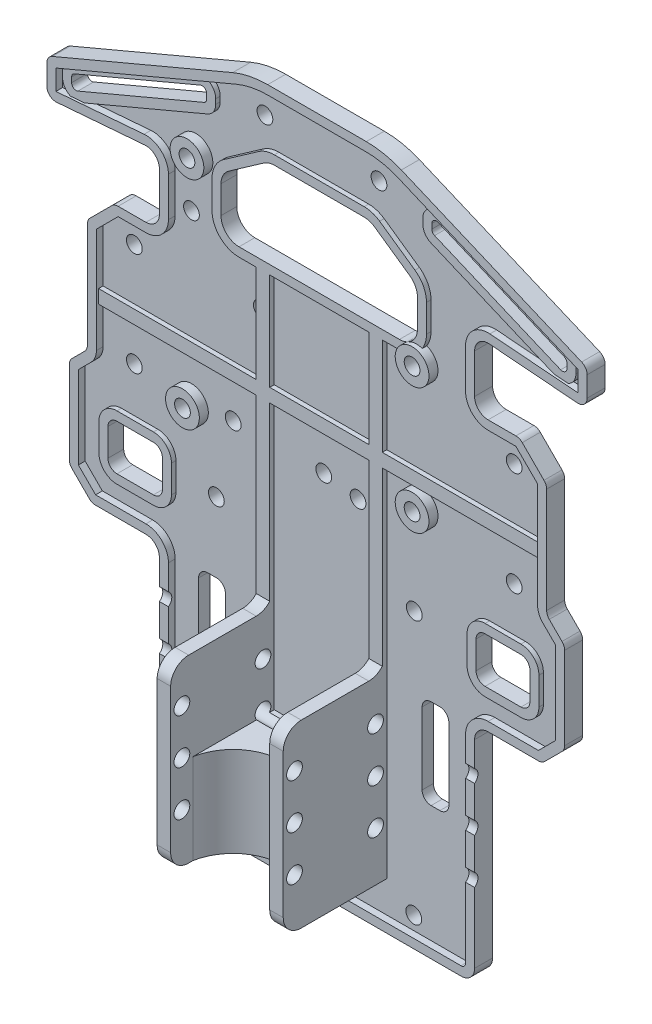
SolidWorks part; units mm, degrees
ref_plane "Front Plane" through (0, 0, 0) normal (0, 0, 1) x (1, 0, 0)
ref_plane "Top Plane" through (0, 0, 0) normal (0, 1, 0) x (1, 0, 0)
ref_plane "Right Plane" through (0, 0, 0) normal (1, 0, 0) x (0, 0, -1)
sketch "Sketch1" plane through (0, 0, 0) normal (0, 0, 1) x (1, 0, 0)
  line L1 (-55, 30) -> (-35, 30) construction
  line L2 (-55, 30) -> (-55, -30) construction
  line L3 (-55, -30) -> (-35, -30) construction
  line L4 (55, 30) -> (55, -30) construction
  line L5 (-55, 30) -> (55, -30) construction
  line L6 (-55, -30) -> (55, 30) construction
  line L8 (-35, 41.7504) -> (-35, 33)
  line L10 (35, 41.7504) -> (35, 33)
  line L11 (-35, 45) -> (35, 30) construction
  line L12 (-35, 30) -> (35, 45) construction
  line L13 (-60, 70) -> (60, 70) construction
  line L14 (-60, 70) -> (-60, 45) construction
  line L15 (-60, 45) -> (-35, 45) construction
  line L16 (60, 70) -> (60, 45) construction
  line L17 (-60, 70) -> (60, 45) construction
  line L18 (-60, 45) -> (60, 70) construction
  line L20 (0, 57.5) -> (0, 37.5) construction
  line L21 (32, -80) -> (-32, -80)
  line L22 (35, -77) -> (35, -33)
  line L24 (-35, -77) -> (-35, -33)
  line L25 (35, -80) -> (-35, -30) construction
  line L26 (35, -30) -> (-35, -80) construction
  line L27 (0, 37.5) -> (0, 0) construction
  line L28 (0, 0) -> (0, -55) construction
  line L29 (35, 45) -> (60, 45) construction
  line L30 (35, 30) -> (55, 30) construction
  line L31 (35, -30) -> (55, -30) construction
  line L32 (-35, -30) -> (35, -30) construction
  line L33 (35, 30) -> (-35, 30) construction
  line L34 (-35, 45) -> (35, 45) construction
  line L35 (-60, 45.1664) -> (-60, 49.6735)
  line L36 (-58.7779, 51.516) -> (-18.7303, 68.425)
  line L37 (-10.9508, 70) -> (10.9508, 70)
  line L38 (18.7303, 68.425) -> (58.7779, 51.516)
  line L39 (60, 49.6735) -> (60, 45.1664)
  line L40 (57.8405, 43.1728) -> (38.2392, 44.7409)
  line L41 (-38.2392, 44.7409) -> (-57.8405, 43.1728)
  line L42 (-60, 51) -> (60, 51) construction
  line L43 (60, 43) -> (-60, 43) construction
  line L44 (0, 57.5) -> (0, 70) construction
  line L45 (-38, -30) -> (-49.1716, -30)
  line L46 (-50.5858, -29.4142) -> (-54.4142, -25.5858)
  line L47 (-55, -24.1716) -> (-55, -5.8284)
  line L48 (-54.4142, -4.4142) -> (-51.5858, -1.5858)
  line L49 (-51, -0.1716) -> (-51, 23.1716)
  line L50 (-50.4142, 24.5858) -> (-45.5858, 29.4142)
  line L51 (-44.1716, 30) -> (-38, 30)
  line L52 (0, -55) -> (0, 55) construction
  line L53 (44.1716, 30) -> (38, 30)
  line L54 (50.4142, 24.5858) -> (45.5858, 29.4142)
  line L55 (51, -0.1716) -> (51, 23.1716)
  line L56 (54.4142, -4.4142) -> (51.5858, -1.5858)
  line L57 (55, -24.1716) -> (55, -5.8284)
  line L58 (50.5858, -29.4142) -> (54.4142, -25.5858)
  line L59 (38, -30) -> (49.1716, -30)
  line L60 (-55, 0) -> (55, 0) construction
  arc A0 (60, 45.1664) -> (57.8405, 43.1728) centre (58, 45.1664) cw
  arc A1 (58.7779, 51.516) -> (60, 49.6735) centre (58, 49.6735) cw
  arc A2 (-60, 45.1664) -> (-57.8405, 43.1728) centre (-58, 45.1664) ccw
  arc A3 (-60, 49.6735) -> (-58.7779, 51.516) centre (-58, 49.6735) cw
  arc A4 (10.9508, 70) -> (18.7303, 68.425) centre (10.9508, 50) cw
  arc A5 (-18.7303, 68.425) -> (-10.9508, 70) centre (-10.9508, 50) cw
  arc A6 (-45.5858, 29.4142) -> (-44.1716, 30) centre (-44.1716, 28) cw
  arc A7 (-51, 23.1716) -> (-50.4142, 24.5858) centre (-49, 23.1716) cw
  arc A8 (-51.5858, -1.5858) -> (-51, -0.1716) centre (-53, -0.1716) ccw
  arc A9 (-55, -5.8284) -> (-54.4142, -4.4142) centre (-53, -5.8284) cw
  arc A10 (-54.4142, -25.5858) -> (-55, -24.1716) centre (-53, -24.1716) cw
  arc A11 (-49.1716, -30) -> (-50.5858, -29.4142) centre (-49.1716, -28) cw
  arc A12 (45.5858, 29.4142) -> (44.1716, 30) centre (44.1716, 28) ccw
  arc A13 (51, 23.1716) -> (50.4142, 24.5858) centre (49, 23.1716) ccw
  arc A14 (51.5858, -1.5858) -> (51, -0.1716) centre (53, -0.1716) cw
  arc A15 (55, -5.8284) -> (54.4142, -4.4142) centre (53, -5.8284) ccw
  arc A16 (54.4142, -25.5858) -> (55, -24.1716) centre (53, -24.1716) ccw
  arc A17 (49.1716, -30) -> (50.5858, -29.4142) centre (49.1716, -28) ccw
  arc A18 (32, -80) -> (35, -77) centre (32, -77) ccw
  arc A19 (-32, -80) -> (-35, -77) centre (-32, -77) cw
  arc A20 (38.2392, 44.7409) -> (35, 41.7504) centre (38, 41.7504) ccw
  arc A21 (38, 30) -> (35, 33) centre (38, 33) cw
  arc A22 (-35, 33) -> (-38, 30) centre (-38, 33) cw
  arc A23 (-38.2392, 44.7409) -> (-35, 41.7504) centre (-38, 41.7504) cw
  arc A24 (35, -33) -> (38, -30) centre (38, -33) cw
  arc A25 (-38, -30) -> (-35, -33) centre (-38, -33) cw
  point P0 (0, 0)
  point P6 (0, 37.5)
  point P11 (0, 57.5)
  point P16 (0, -55)
  point P46 (15, 70)
  point P49 (-15, 70)
  point P58 (-45, 30)
  point P61 (-51, 24)
  point P64 (-51, -1)
  point P67 (-55, -5)
  point P70 (-55, -25)
  point P73 (-50, -30)
  dimension "D11" = 2
  dimension "D12" = 20
  dimension "D20" = 2
  dimension "D21" = 3
  dimension "D1" = 120
  dimension "D2" = 25
  dimension "D3" = 15
  dimension "D4" = 60
  dimension "D5" = 50
  dimension "D6" = 70
  dimension "D7" = 70
  dimension "D8" = 2
  dimension "D9" = 8
  dimension "D10" = 30
  dimension "D13" = 15
  dimension "D14" = 45
  dimension "D15" = 20
  dimension "D16" = 45
  dimension "D17" = 45
  dimension "D18" = 25
  dimension "D19" = 4
  dimension "D22" = 110
extrude "Boss-Extrude1" add sketch "Sketch1" along normal blind 2.5
sketch "Sketch14" plane through (0, 0, 2.5) normal (0, 0, 1) x (1, 0, 0)
  line L0 (-53.611, 47.1847) -> (-25.611, 59.0069)
  line L1 (-25, 59.9281) -> (-25, 61.0136)
  line L2 (-26.389, 61.9349) -> (-54.389, 50.1127)
  line L3 (-55, 49.1914) -> (-55, 48.1059)
  line L4 (-18.7303, 68.425) -> (-58.7779, 51.516) construction
  line L5 (0, -55) -> (0, 55) construction
  line L6 (55, 49.1914) -> (55, 48.1059)
  line L7 (26.389, 61.9349) -> (54.389, 50.1127)
  line L8 (25, 59.9281) -> (25, 61.0136)
  line L9 (53.611, 47.1847) -> (25.611, 59.0069)
  arc A0 (-25.611, 59.0069) -> (-25, 59.9281) centre (-26, 59.9281) ccw
  arc A1 (-25, 61.0136) -> (-26.389, 61.9349) centre (-26, 61.0136) ccw
  arc A2 (-53.611, 47.1847) -> (-55, 48.1059) centre (-54, 48.1059) cw
  arc A3 (-54.389, 50.1127) -> (-55, 49.1914) centre (-54, 49.1914) ccw
  arc A4 (54.389, 50.1127) -> (55, 49.1914) centre (54, 49.1914) cw
  arc A5 (53.611, 47.1847) -> (55, 48.1059) centre (54, 48.1059) ccw
  arc A6 (25, 61.0136) -> (26.389, 61.9349) centre (26, 61.0136) cw
  arc A7 (25.611, 59.0069) -> (25, 59.9281) centre (26, 59.9281) cw
  point P14 (-25, 60.4709)
  dimension "D1" = 1
  dimension "D2" = 3
  dimension "D3" = 30
  dimension "D4" = 3
  dimension "D5" = 25
extrude "Cut-Extrude6" cut sketch "Sketch14" against normal through all
sketch "Sketch17" plane through (0, 0, 2.5) normal (0, 0, 1) x (1, 0, 0)
  line L0 (21.6202, 4.389) -> (21.6202, 32.389) construction
  line L1 (-29.3798, 35.789) -> (-29.3798, -1.211) construction
  line L2 (-29.3798, -1.211) -> (7.6202, -1.211) construction
  line L3 (7.6202, -1.211) -> (7.6202, 35.789) construction
  line L4 (7.6202, 35.789) -> (-29.3798, 35.789) construction
  line L6 (24.6202, 4.389) -> (21.6202, 4.389) construction
  circle A0 centre (21.6202, 32.389) radius 1.75
  circle A1 centre (21.6202, 4.389) radius 1.75
  circle A2 centre (-29.3798, -1.211) radius 1.75
  circle A3 centre (-28.3798, 47.389) radius 1.75
  circle A4 centre (-29.3798, 35.789) radius 1.75
  circle A6 centre (7.6202, -1.211) radius 1.75
  dimension "D1" = 3.5
  dimension "D2" = 3.5
  dimension "D3" = 3.5
  dimension "D6" = 3.5
  dimension "D8" = 3.5
  dimension "D4" = 37
  dimension "D5" = 37
  dimension "D10" = 3
  dimension "D11" = 28
  dimension "D12" = 15
  dimension "D13" = 5.6
  dimension "D14" = 50
  dimension "D15" = 51
extrude "Cut-Extrude8" cut sketch "Sketch17" against normal through all both and the other way through all
ref_plane "Plane1" through (-35, -33, 2.5) normal (0, -1, 0) x (-1, 0, 0)
sketch "Sketch19" plane through (0, 0, 2.5) normal (0, 0, 1) x (1, 0, 0)
  line L0 (58, 45.1664) -> (58, 49.6735)
  line L1 (58, 49.6735) -> (17.9523, 66.5825)
  line L2 (10.9508, 68) -> (-10.9508, 68)
  line L3 (-17.9523, 66.5825) -> (-58, 49.6735)
  line L4 (-58, 49.6735) -> (-58, 45.1664)
  line L5 (-58, 45.1664) -> (-38.3987, 46.7345)
  line L6 (-33, 41.7504) -> (-33, 33)
  line L7 (-38, 28) -> (-44.1716, 28)
  line L8 (-44.1716, 28) -> (-49, 23.1716)
  line L9 (-49, 23.1716) -> (-49, -0.1716)
  line L10 (-50.1716, -3) -> (-53, -5.8284)
  line L11 (-53, -5.8284) -> (-53, -24.1716)
  line L12 (-53, -24.1716) -> (-49.1716, -28)
  line L13 (-49.1716, -28) -> (-38, -28)
  line L14 (-33, -33) -> (-33, -77)
  line L15 (-32, -78) -> (32, -78)
  line L16 (33, -77) -> (33, -33)
  line L17 (38, -28) -> (49.1716, -28)
  line L18 (49.1716, -28) -> (53, -24.1716)
  line L19 (53, -24.1716) -> (53, -5.8284)
  line L20 (53, -5.8284) -> (50.1716, -3)
  line L21 (49, -0.1716) -> (49, 23.1716)
  line L22 (49, 23.1716) -> (44.1716, 28)
  line L23 (44.1716, 28) -> (38, 28)
  line L24 (33, 33) -> (33, 41.7504)
  line L25 (38.3987, 46.7345) -> (58, 45.1664)
  line L26 (60, 45.1664) -> (60, 49.6735)
  line L27 (58.7779, 51.516) -> (18.7303, 68.425)
  line L28 (10.9508, 70) -> (-10.9508, 70)
  line L29 (-18.7303, 68.425) -> (-58.7779, 51.516)
  line L30 (-60, 49.6735) -> (-60, 45.1664)
  line L31 (-57.8405, 43.1728) -> (-38.2392, 44.7409)
  line L32 (-35, 41.7504) -> (-35, 33)
  line L33 (-38, 30) -> (-44.1716, 30)
  line L34 (-45.5858, 29.4142) -> (-50.4142, 24.5858)
  line L35 (-51, 23.1716) -> (-51, -0.1716)
  line L36 (-51.5858, -1.5858) -> (-54.4142, -4.4142)
  line L37 (-55, -5.8284) -> (-55, -24.1716)
  line L38 (-54.4142, -25.5858) -> (-50.5858, -29.4142)
  line L39 (-49.1716, -30) -> (-38, -30)
  line L40 (-35, -33) -> (-35, -77)
  line L41 (-32, -80) -> (32, -80)
  line L42 (35, -77) -> (35, -33)
  line L43 (38, -30) -> (49.1716, -30)
  line L44 (50.5858, -29.4142) -> (54.4142, -25.5858)
  line L45 (55, -24.1716) -> (55, -5.8284)
  line L46 (54.4142, -4.4142) -> (51.5858, -1.5858)
  line L47 (51, -0.1716) -> (51, 23.1716)
  line L48 (50.4142, 24.5858) -> (45.5858, 29.4142)
  line L49 (44.1716, 30) -> (38, 30)
  line L50 (35, 33) -> (35, 41.7504)
  line L51 (38.2392, 44.7409) -> (57.8405, 43.1728)
  line L52 (60, 45.1664) -> (60, 49.6735)
  line L53 (58.7779, 51.516) -> (18.7303, 68.425)
  line L54 (10.9508, 70) -> (-10.9508, 70)
  line L55 (-18.7303, 68.425) -> (-58.7779, 51.516)
  line L56 (-60, 49.6735) -> (-60, 45.1664)
  line L57 (-57.8405, 43.1728) -> (-38.2392, 44.7409)
  line L58 (-35, 41.7504) -> (-35, 33)
  line L59 (-38, 30) -> (-44.1716, 30)
  line L60 (-45.5858, 29.4142) -> (-50.4142, 24.5858)
  line L61 (-51, 23.1716) -> (-51, -0.1716)
  line L62 (-51.5858, -1.5858) -> (-54.4142, -4.4142)
  line L63 (-55, -5.8284) -> (-55, -24.1716)
  line L64 (-54.4142, -25.5858) -> (-50.5858, -29.4142)
  line L65 (-49.1716, -30) -> (-38, -30)
  line L66 (-35, -33) -> (-35, -77)
  line L67 (-32, -80) -> (32, -80)
  line L68 (35, -77) -> (35, -33)
  line L69 (38, -30) -> (49.1716, -30)
  line L70 (50.5858, -29.4142) -> (54.4142, -25.5858)
  line L71 (55, -24.1716) -> (55, -5.8284)
  line L72 (54.4142, -4.4142) -> (51.5858, -1.5858)
  line L73 (51, -0.1716) -> (51, 23.1716)
  line L74 (50.4142, 24.5858) -> (45.5858, 29.4142)
  line L75 (44.1716, 30) -> (38, 30)
  line L76 (35, 33) -> (35, 41.7504)
  line L77 (38.2392, 44.7409) -> (57.8405, 43.1728)
  arc A0 (58, 49.6735) -> (58, 49.6735) centre (58, 49.6735) ccw
  arc A1 (17.9523, 66.5825) -> (10.9508, 68) centre (10.9508, 50) ccw
  arc A2 (-10.9508, 68) -> (-17.9523, 66.5825) centre (-10.9508, 50) ccw
  arc A3 (-58, 49.6735) -> (-58, 49.6735) centre (-58, 49.6735) ccw
  arc A4 (-58, 45.1664) -> (-58, 45.1664) centre (-58, 45.1664) ccw
  arc A5 (-33, 41.7504) -> (-38.3987, 46.7345) centre (-38, 41.7504) ccw
  arc A6 (-38, 28) -> (-33, 33) centre (-38, 33) ccw
  arc A7 (-44.1716, 28) -> (-44.1716, 28) centre (-44.1716, 28) ccw
  arc A8 (-49, 23.1716) -> (-49, 23.1716) centre (-49, 23.1716) ccw
  arc A9 (-50.1716, -3) -> (-49, -0.1716) centre (-53, -0.1716) ccw
  arc A10 (-53, -5.8284) -> (-53, -5.8284) centre (-53, -5.8284) ccw
  arc A11 (-53, -24.1716) -> (-53, -24.1716) centre (-53, -24.1716) ccw
  arc A12 (-49.1716, -28) -> (-49.1716, -28) centre (-49.1716, -28) ccw
  arc A13 (-33, -33) -> (-38, -28) centre (-38, -33) ccw
  arc A14 (-33, -77) -> (-32, -78) centre (-32, -77) ccw
  arc A15 (32, -78) -> (33, -77) centre (32, -77) ccw
  arc A16 (38, -28) -> (33, -33) centre (38, -33) ccw
  arc A17 (49.1716, -28) -> (49.1716, -28) centre (49.1716, -28) ccw
  arc A18 (53, -24.1716) -> (53, -24.1716) centre (53, -24.1716) ccw
  arc A19 (53, -5.8284) -> (53, -5.8284) centre (53, -5.8284) ccw
  arc A20 (49, -0.1716) -> (50.1716, -3) centre (53, -0.1716) ccw
  arc A21 (49, 23.1716) -> (49, 23.1716) centre (49, 23.1716) ccw
  arc A22 (44.1716, 28) -> (44.1716, 28) centre (44.1716, 28) ccw
  arc A23 (33, 33) -> (38, 28) centre (38, 33) ccw
  arc A24 (38.3987, 46.7345) -> (33, 41.7504) centre (38, 41.7504) ccw
  arc A25 (58, 45.1664) -> (58, 45.1664) centre (58, 45.1664) ccw
  arc A26 (57.8405, 43.1728) -> (60, 45.1664) centre (58, 45.1664) ccw
  arc A27 (60, 49.6735) -> (58.7779, 51.516) centre (58, 49.6735) ccw
  arc A28 (18.7303, 68.425) -> (10.9508, 70) centre (10.9508, 50) ccw
  arc A29 (-10.9508, 70) -> (-18.7303, 68.425) centre (-10.9508, 50) ccw
  arc A30 (-58.7779, 51.516) -> (-60, 49.6735) centre (-58, 49.6735) ccw
  arc A31 (-60, 45.1664) -> (-57.8405, 43.1728) centre (-58, 45.1664) ccw
  arc A32 (-35, 41.7504) -> (-38.2392, 44.7409) centre (-38, 41.7504) ccw
  arc A33 (-38, 30) -> (-35, 33) centre (-38, 33) ccw
  arc A34 (-44.1716, 30) -> (-45.5858, 29.4142) centre (-44.1716, 28) ccw
  arc A35 (-50.4142, 24.5858) -> (-51, 23.1716) centre (-49, 23.1716) ccw
  arc A36 (-51.5858, -1.5858) -> (-51, -0.1716) centre (-53, -0.1716) ccw
  arc A37 (-54.4142, -4.4142) -> (-55, -5.8284) centre (-53, -5.8284) ccw
  arc A38 (-55, -24.1716) -> (-54.4142, -25.5858) centre (-53, -24.1716) ccw
  arc A39 (-50.5858, -29.4142) -> (-49.1716, -30) centre (-49.1716, -28) ccw
  arc A40 (-35, -33) -> (-38, -30) centre (-38, -33) ccw
  arc A41 (-35, -77) -> (-32, -80) centre (-32, -77) ccw
  arc A42 (32, -80) -> (35, -77) centre (32, -77) ccw
  arc A43 (38, -30) -> (35, -33) centre (38, -33) ccw
  arc A44 (49.1716, -30) -> (50.5858, -29.4142) centre (49.1716, -28) ccw
  arc A45 (54.4142, -25.5858) -> (55, -24.1716) centre (53, -24.1716) ccw
  arc A46 (55, -5.8284) -> (54.4142, -4.4142) centre (53, -5.8284) ccw
  arc A47 (51, -0.1716) -> (51.5858, -1.5858) centre (53, -0.1716) ccw
  arc A48 (51, 23.1716) -> (50.4142, 24.5858) centre (49, 23.1716) ccw
  arc A49 (45.5858, 29.4142) -> (44.1716, 30) centre (44.1716, 28) ccw
  arc A50 (35, 33) -> (38, 30) centre (38, 33) ccw
  arc A51 (38.2392, 44.7409) -> (35, 41.7504) centre (38, 41.7504) ccw
  arc A52 (57.8405, 43.1728) -> (60, 45.1664) centre (58, 45.1664) ccw
  arc A53 (60, 49.6735) -> (58.7779, 51.516) centre (58, 49.6735) ccw
  arc A54 (18.7303, 68.425) -> (10.9508, 70) centre (10.9508, 50) ccw
  arc A55 (-10.9508, 70) -> (-18.7303, 68.425) centre (-10.9508, 50) ccw
  arc A56 (-58.7779, 51.516) -> (-60, 49.6735) centre (-58, 49.6735) ccw
  arc A57 (-60, 45.1664) -> (-57.8405, 43.1728) centre (-58, 45.1664) ccw
  arc A58 (-35, 41.7504) -> (-38.2392, 44.7409) centre (-38, 41.7504) ccw
  arc A59 (-38, 30) -> (-35, 33) centre (-38, 33) ccw
  arc A60 (-44.1716, 30) -> (-45.5858, 29.4142) centre (-44.1716, 28) ccw
  arc A61 (-50.4142, 24.5858) -> (-51, 23.1716) centre (-49, 23.1716) ccw
  arc A62 (-51.5858, -1.5858) -> (-51, -0.1716) centre (-53, -0.1716) ccw
  arc A63 (-54.4142, -4.4142) -> (-55, -5.8284) centre (-53, -5.8284) ccw
  arc A64 (-55, -24.1716) -> (-54.4142, -25.5858) centre (-53, -24.1716) ccw
  arc A65 (-50.5858, -29.4142) -> (-49.1716, -30) centre (-49.1716, -28) ccw
  arc A66 (-35, -33) -> (-38, -30) centre (-38, -33) ccw
  arc A67 (-35, -77) -> (-32, -80) centre (-32, -77) ccw
  arc A68 (32, -80) -> (35, -77) centre (32, -77) ccw
  arc A69 (38, -30) -> (35, -33) centre (38, -33) ccw
  arc A70 (49.1716, -30) -> (50.5858, -29.4142) centre (49.1716, -28) ccw
  arc A71 (54.4142, -25.5858) -> (55, -24.1716) centre (53, -24.1716) ccw
  arc A72 (55, -5.8284) -> (54.4142, -4.4142) centre (53, -5.8284) ccw
  arc A73 (51, -0.1716) -> (51.5858, -1.5858) centre (53, -0.1716) ccw
  arc A74 (51, 23.1716) -> (50.4142, 24.5858) centre (49, 23.1716) ccw
  arc A75 (45.5858, 29.4142) -> (44.1716, 30) centre (44.1716, 28) ccw
  arc A76 (35, 33) -> (38, 30) centre (38, 33) ccw
  arc A77 (38.2392, 44.7409) -> (35, 41.7504) centre (38, 41.7504) ccw
  dimension "D1" = 0
  dimension "D2" = 2
extrude "Boss-Extrude2" add sketch "Sketch19" along normal blind 1.5
sketch "Sketch20" plane through (0, 0, 2.5) normal (0, 0, 1) x (1, 0, 0)
  line L0 (-20.1087, 48.5343) -> (-12.2683, 54.0191)
  line L2 (-21.8159, 45.2567) -> (-21.8159, 39.1272)
  line L3 (-17.8159, 35.1272) -> (17.8159, 35.1272)
  line L4 (21.8159, 45.2567) -> (21.8159, 39.1272)
  line L5 (-21.8159, 47.3401) -> (21.8159, 35.1272) construction
  line L6 (-21.8159, 35.1272) -> (21.8159, 47.3401) construction
  line L7 (-9.9754, 54.7415) -> (9.9754, 54.7415)
  line L8 (12.2683, 54.0191) -> (20.1087, 48.5343)
  line L9 (0, 0) -> (0, 41.2337) construction
  line L10 (0, 41.2337) -> (0, 54.7415) construction
  line L11 (-21.8451, -32.0477) -> (21.8451, -32.0477) construction
  line L16 (23.8451, -32.0477) -> (25.7855, -32.0477)
  line L17 (21.8451, -34.0477) -> (21.8451, -50.0121)
  line L18 (23.8451, -52.0121) -> (25.7855, -52.0121)
  line L19 (27.7855, -34.0477) -> (27.7855, -50.0121)
  line L20 (-25.7943, -32.0477) -> (-23.8451, -32.0477)
  line L21 (-27.7943, -34.0477) -> (-27.7943, -50.0121)
  line L22 (-25.7943, -52.0121) -> (-23.8451, -52.0121)
  line L23 (-21.8451, -34.0477) -> (-21.8451, -50.0121)
  line L24 (-21.8451, -52.0121) -> (27.7855, -52.0121) construction
  line L25 (0, -32.0477) -> (0, 0) construction
  line L26 (0, 0) -> (0, 9.9481) construction
  line L27 (-34.8257, -11.9839) -> (34.8257, -11.9839) construction
  line L28 (44.7902, -11.9839) -> (36.8257, -11.9839)
  line L29 (46.7902, -13.9839) -> (46.7902, -20.0923)
  line L30 (44.7902, -22.0923) -> (36.8257, -22.0923)
  line L31 (34.8257, -13.9839) -> (34.8257, -20.0923)
  line L32 (-36.8257, -11.9839) -> (-44.9308, -11.9839)
  line L33 (-34.8257, -13.9839) -> (-34.8257, -20.0923)
  line L34 (-36.8257, -22.0923) -> (-44.9308, -22.0923)
  line L35 (-46.9308, -13.9839) -> (-46.9308, -20.0923)
  line L36 (34.8257, -22.0923) -> (-34.8257, -22.0923) construction
  line L37 (0, -11.9839) -> (0, 0) construction
  line L38 (-32, -80) -> (32, -80) construction
  line L39 (-35, -33) -> (-35, -77) construction
  line L43 (0, 14.5554) -> (0, 0) construction
  arc A0 (-20.1087, 48.5343) -> (-21.8159, 45.2567) centre (-17.8159, 45.2567) ccw
  arc A1 (-21.8159, 39.1272) -> (-17.8159, 35.1272) centre (-17.8159, 39.1272) ccw
  arc A2 (17.8159, 35.1272) -> (21.8159, 39.1272) centre (17.8159, 39.1272) ccw
  arc A3 (20.1087, 48.5343) -> (21.8159, 45.2567) centre (17.8159, 45.2567) cw
  arc A4 (9.9754, 54.7415) -> (12.2683, 54.0191) centre (9.9754, 50.7415) cw
  arc A5 (-12.2683, 54.0191) -> (-9.9754, 54.7415) centre (-9.9754, 50.7415) cw
  arc A6 (21.8451, -50.0121) -> (23.8451, -52.0121) centre (23.8451, -50.0121) ccw
  arc A7 (25.7855, -52.0121) -> (27.7855, -50.0121) centre (25.7855, -50.0121) ccw
  arc A8 (25.7855, -32.0477) -> (27.7855, -34.0477) centre (25.7855, -34.0477) cw
  arc A9 (23.8451, -32.0477) -> (21.8451, -34.0477) centre (23.8451, -34.0477) ccw
  arc A10 (-27.7943, -50.0121) -> (-25.7943, -52.0121) centre (-25.7943, -50.0121) ccw
  arc A11 (-23.8451, -52.0121) -> (-21.8451, -50.0121) centre (-23.8451, -50.0121) ccw
  arc A12 (-23.8451, -32.0477) -> (-21.8451, -34.0477) centre (-23.8451, -34.0477) cw
  arc A13 (-25.7943, -32.0477) -> (-27.7943, -34.0477) centre (-25.7943, -34.0477) ccw
  arc A18 (46.7902, -20.0923) -> (44.7902, -22.0923) centre (44.7902, -20.0923) cw
  arc A19 (44.7902, -11.9839) -> (46.7902, -13.9839) centre (44.7902, -13.9839) cw
  arc A20 (36.8257, -11.9839) -> (34.8257, -13.9839) centre (36.8257, -13.9839) ccw
  arc A21 (36.8257, -22.0923) -> (34.8257, -20.0923) centre (36.8257, -20.0923) cw
  arc A22 (-34.8257, -20.0923) -> (-36.8257, -22.0923) centre (-36.8257, -20.0923) cw
  arc A23 (-36.8257, -11.9839) -> (-34.8257, -13.9839) centre (-36.8257, -13.9839) cw
  arc A24 (-44.9308, -11.9839) -> (-46.9308, -13.9839) centre (-44.9308, -13.9839) ccw
  arc A25 (-44.9308, -22.0923) -> (-46.9308, -20.0923) centre (-44.9308, -20.0923) cw
  circle A26 centre (-42.0638, 22.9587) radius 1.75
  circle A27 centre (42.2976, 22.9587) radius 1.75
  circle A28 centre (42.2976, -0.1284) radius 1.75
  circle A29 centre (-42.0638, 0) radius 1.75
  circle A30 centre (-23.8451, -16.4765) radius 1.75
  circle A31 centre (20.1087, -16.4765) radius 1.75
  circle A32 centre (-20.1087, 0) radius 1.75
  circle A33 centre (-13.8601, 24.581) radius 1.75
  circle A34 centre (-13.0606, 62.3533) radius 1.75
  circle A35 centre (12.2683, 62.3533) radius 1.75
  circle A36 centre (0, 0) radius 1.75
  circle A37 centre (-25, -75) radius 1.75
  circle A38 centre (-10, -75) radius 1.75
  circle A39 centre (5, -75) radius 1.75
  circle A40 centre (20, -75) radius 1.75
  circle A47 centre (35, -75) radius 1.75 [skipped]
  circle A48 centre (50, -75) radius 1.75 [skipped]
  point P0 (0, 41.2337)
  dimension "D1" = 4
  dimension "D2" = 2
  dimension "D3" = 2
  dimension "D4" = 3.5
  dimension "D5" = 5
  dimension "D6" = 10
  dimension "D7" = 6
extrude "Cut-Extrude9" cut sketch "Sketch20" against normal through all
sketch "Sketch21" plane through (0, 0, 2.5) normal (0, 0, 1) x (1, 0, 0)
  line L1 (-14, -71) -> (-11, -71)
  line L2 (-14, -71) -> (-14, -31)
  line L3 (-14, -31) -> (-11, -31)
  line L4 (-11, -51) -> (-11, -31)
  line L5 (-11, -31) -> (11, -31) construction
  line L6 (14, -71) -> (11, -71)
  line L7 (14, -71) -> (14, -31)
  line L8 (14, -31) -> (11, -31)
  line L9 (11, -51) -> (11, -31)
  line L10 (-33, -33) -> (-33, -77) construction
  line L11 (33, -77) -> (33, -33) construction
  line L12 (-11, -51) -> (11, -51)
  line L13 (-11, -71) -> (11, -71)
  line L14 (-32, -78) -> (32, -78) construction
  dimension "D1" = 19
  dimension "D2" = 19
  dimension "D3" = 3
  dimension "D4" = 3
  dimension "D5" = 40
  dimension "D6" = 20
  dimension "D7" = 7
extrude "Boss-Extrude3" add sketch "Sketch21" along normal blind 23
sketch "Sketch22" plane through (0, -71, 0) normal (0, -1, 0) x (1, 0, 0)
  line L0 (-14, 25.5) -> (14, 25.5) construction
  line L2 (-11, 20.5) -> (-11, 25.5)
  line L3 (-11, 25.5) -> (11, 25.5)
  line L4 (11, 25.5) -> (11, 20.5)
  line L5 (-14, 25.5) -> (-14, 2.5) construction
  line L6 (14, 25.5) -> (14, 2.5) construction
  line L7 (-11, 20.5) -> (11, 20.5) construction
  arc A0 (-11, 20.5) -> (11, 20.5) centre (0, 22.6283) ccw
  dimension "D1" = 3
  dimension "D2" = 3
  dimension "D3" = 5
extrude "Cut-Extrude10" cut sketch "Sketch22" against normal blind 33
sketch "Sketch23" plane through (-14, 0, 0) normal (-1, 0, 0) x (0, 0, 1)
  line L0 (5, -40) -> (23, -40) construction
  line L1 (14, -31) -> (14, -40) construction
  line L2 (25.5, -31) -> (2.5, -31) construction
  line L3 (4, -80) -> (0, -80) construction
  circle A0 centre (5, -40) radius 1.75
  circle A1 centre (23, -40) radius 1.75
  dimension "D2" = 3.5
  dimension "D1" = 18
  dimension "D3" = 40
extrude "Cut-Extrude11" cut sketch "Sketch23" against normal through all both and the other way through all
pattern_linear "LPattern1" count 3 spacing 10 along (0, -1, 0) of "Cut-Extrude11"
fillet "Fillet1" radius 4 6 edges at (-12.5, -71, 25.5) (12.5, -71, 25.5) (-12.5, -31, 2.5) (-12.5, -31, 25.5) (12.5, -31, 2.5) (12.5, -31, 25.5)
sketch "Sketch24" plane through (0, 0, 2.5) normal (0, 0, 1) x (1, 0, 0)
  line L0 (48.7902, -20.0923) -> (48.7902, -13.9839)
  line L1 (44.7902, -9.9839) -> (36.8257, -9.9839)
  line L2 (32.8257, -13.9839) -> (32.8257, -20.0923)
  line L3 (36.8257, -24.0923) -> (44.7902, -24.0923)
  line L4 (46.7902, -20.0923) -> (46.7902, -13.9839)
  line L5 (36.8257, -22.0923) -> (44.7902, -22.0923)
  line L6 (34.8257, -13.9839) -> (34.8257, -20.0923)
  line L7 (44.7902, -11.9839) -> (36.8257, -11.9839)
  line L8 (46.7902, -20.0923) -> (46.7902, -13.9839)
  line L9 (36.8257, -22.0923) -> (44.7902, -22.0923)
  line L10 (34.8257, -13.9839) -> (34.8257, -20.0923)
  line L11 (44.7902, -11.9839) -> (36.8257, -11.9839)
  line L12 (-34.8257, -20.0923) -> (-34.8257, -13.9839)
  line L13 (-44.9308, -22.0923) -> (-36.8257, -22.0923)
  line L14 (-46.9308, -13.9839) -> (-46.9308, -20.0923)
  line L15 (-36.8257, -11.9839) -> (-44.9308, -11.9839)
  line L16 (-34.8257, -20.0923) -> (-34.8257, -13.9839)
  line L17 (-44.9308, -22.0923) -> (-36.8257, -22.0923)
  line L18 (-46.9308, -13.9839) -> (-46.9308, -20.0923)
  line L19 (-36.8257, -11.9839) -> (-44.9308, -11.9839)
  line L20 (-25, 59.9281) -> (-25, 61.0136)
  line L21 (-53.611, 47.1847) -> (-25.611, 59.0069)
  line L22 (-55, 49.1914) -> (-55, 48.1059)
  line L23 (-26.389, 61.9349) -> (-54.389, 50.1127)
  line L24 (-25, 59.9281) -> (-25, 61.0136)
  line L25 (-53.611, 47.1847) -> (-25.611, 59.0069)
  line L26 (-55, 49.1914) -> (-55, 48.1059)
  line L27 (-26.389, 61.9349) -> (-54.389, 50.1127)
  line L28 (54.389, 50.1127) -> (26.389, 61.9349)
  line L29 (55, 48.1059) -> (55, 49.1914)
  line L30 (25.611, 59.0069) -> (53.611, 47.1847)
  line L31 (25, 61.0136) -> (25, 59.9281)
  line L32 (54.389, 50.1127) -> (26.389, 61.9349)
  line L33 (55, 48.1059) -> (55, 49.1914)
  line L34 (25.611, 59.0069) -> (53.611, 47.1847)
  line L35 (25, 61.0136) -> (25, 59.9281)
  line L37 (-17.8159, 33.1272) -> (17.8159, 33.1272)
  line L39 (23.8159, 39.1272) -> (23.8159, 45.2567)
  line L40 (21.2551, 50.1732) -> (13.4147, 55.6579)
  line L41 (9.9754, 56.7415) -> (-9.9754, 56.7415)
  line L56 (-32.8257, -20.0923) -> (-32.8257, -13.9839)
  line L57 (-36.8257, -9.9839) -> (-44.9308, -9.9839)
  line L58 (-48.9308, -13.9839) -> (-48.9308, -20.0923)
  line L59 (-44.9308, -24.0923) -> (-36.8257, -24.0923)
  line L60 (-23, 59.9281) -> (-23, 61.0136)
  line L61 (-27.1669, 63.7774) -> (-55.1669, 51.9552)
  line L62 (-57, 49.1914) -> (-57, 48.1059)
  line L63 (-52.8331, 45.3422) -> (-24.8331, 57.1644)
  line L64 (55.1669, 51.9552) -> (27.1669, 63.7774)
  line L65 (23, 61.0136) -> (23, 59.9281)
  line L66 (24.8331, 57.1644) -> (52.8331, 45.3422)
  line L67 (57, 48.1059) -> (57, 49.1914)
  line L94 (-13.4147, 55.6579) -> (-21.2551, 50.1732)
  line L95 (-23.8159, 45.2567) -> (-23.8159, 39.1272)
  line L96 (-21.8159, 45.2567) -> (-21.8159, 39.1272)
  line L97 (-12.2683, 54.0191) -> (-20.1087, 48.5343)
  line L98 (9.9754, 54.7415) -> (-9.9754, 54.7415)
  line L99 (20.1087, 48.5343) -> (12.2683, 54.0191)
  line L100 (21.8159, 39.1272) -> (21.8159, 45.2567)
  line L101 (-17.8159, 35.1272) -> (17.8159, 35.1272)
  line L102 (-21.8159, 45.2567) -> (-21.8159, 39.1272)
  line L103 (-12.2683, 54.0191) -> (-20.1087, 48.5343)
  line L104 (9.9754, 54.7415) -> (-9.9754, 54.7415)
  line L105 (20.1087, 48.5343) -> (12.2683, 54.0191)
  line L106 (21.8159, 39.1272) -> (21.8159, 45.2567)
  line L107 (-17.8159, 35.1272) -> (17.8159, 35.1272)
  arc A0 (48.7902, -13.9839) -> (44.7902, -9.9839) centre (44.7902, -13.9839) ccw
  arc A1 (36.8257, -9.9839) -> (32.8257, -13.9839) centre (36.8257, -13.9839) ccw
  arc A2 (32.8257, -20.0923) -> (36.8257, -24.0923) centre (36.8257, -20.0923) ccw
  arc A3 (44.7902, -24.0923) -> (48.7902, -20.0923) centre (44.7902, -20.0923) ccw
  arc A4 (44.7902, -22.0923) -> (46.7902, -20.0923) centre (44.7902, -20.0923) ccw
  arc A5 (34.8257, -20.0923) -> (36.8257, -22.0923) centre (36.8257, -20.0923) ccw
  arc A6 (36.8257, -11.9839) -> (34.8257, -13.9839) centre (36.8257, -13.9839) ccw
  arc A7 (46.7902, -13.9839) -> (44.7902, -11.9839) centre (44.7902, -13.9839) ccw
  arc A8 (44.7902, -22.0923) -> (46.7902, -20.0923) centre (44.7902, -20.0923) ccw
  arc A9 (34.8257, -20.0923) -> (36.8257, -22.0923) centre (36.8257, -20.0923) ccw
  arc A10 (36.8257, -11.9839) -> (34.8257, -13.9839) centre (36.8257, -13.9839) ccw
  arc A11 (46.7902, -13.9839) -> (44.7902, -11.9839) centre (44.7902, -13.9839) ccw
  arc A12 (-36.8257, -22.0923) -> (-34.8257, -20.0923) centre (-36.8257, -20.0923) ccw
  arc A13 (-46.9308, -20.0923) -> (-44.9308, -22.0923) centre (-44.9308, -20.0923) ccw
  arc A14 (-44.9308, -11.9839) -> (-46.9308, -13.9839) centre (-44.9308, -13.9839) ccw
  arc A15 (-34.8257, -13.9839) -> (-36.8257, -11.9839) centre (-36.8257, -13.9839) ccw
  arc A16 (-36.8257, -22.0923) -> (-34.8257, -20.0923) centre (-36.8257, -20.0923) ccw
  arc A17 (-46.9308, -20.0923) -> (-44.9308, -22.0923) centre (-44.9308, -20.0923) ccw
  arc A18 (-44.9308, -11.9839) -> (-46.9308, -13.9839) centre (-44.9308, -13.9839) ccw
  arc A19 (-34.8257, -13.9839) -> (-36.8257, -11.9839) centre (-36.8257, -13.9839) ccw
  arc A20 (-25.611, 59.0069) -> (-25, 59.9281) centre (-26, 59.9281) ccw
  arc A21 (-55, 48.1059) -> (-53.611, 47.1847) centre (-54, 48.1059) ccw
  arc A22 (-54.389, 50.1127) -> (-55, 49.1914) centre (-54, 49.1914) ccw
  arc A23 (-25, 61.0136) -> (-26.389, 61.9349) centre (-26, 61.0136) ccw
  arc A24 (-25.611, 59.0069) -> (-25, 59.9281) centre (-26, 59.9281) ccw
  arc A25 (-55, 48.1059) -> (-53.611, 47.1847) centre (-54, 48.1059) ccw
  arc A26 (-54.389, 50.1127) -> (-55, 49.1914) centre (-54, 49.1914) ccw
  arc A27 (-25, 61.0136) -> (-26.389, 61.9349) centre (-26, 61.0136) ccw
  arc A28 (55, 49.1914) -> (54.389, 50.1127) centre (54, 49.1914) ccw
  arc A29 (53.611, 47.1847) -> (55, 48.1059) centre (54, 48.1059) ccw
  arc A30 (25, 59.9281) -> (25.611, 59.0069) centre (26, 59.9281) ccw
  arc A31 (26.389, 61.9349) -> (25, 61.0136) centre (26, 61.0136) ccw
  arc A32 (55, 49.1914) -> (54.389, 50.1127) centre (54, 49.1914) ccw
  arc A33 (53.611, 47.1847) -> (55, 48.1059) centre (54, 48.1059) ccw
  arc A34 (25, 59.9281) -> (25.611, 59.0069) centre (26, 59.9281) ccw
  arc A35 (26.389, 61.9349) -> (25, 61.0136) centre (26, 61.0136) ccw
  arc A56 (-32.8257, -13.9839) -> (-36.8257, -9.9839) centre (-36.8257, -13.9839) ccw
  arc A57 (-44.9308, -9.9839) -> (-48.9308, -13.9839) centre (-44.9308, -13.9839) ccw
  arc A58 (-48.9308, -20.0923) -> (-44.9308, -24.0923) centre (-44.9308, -20.0923) ccw
  arc A59 (-36.8257, -24.0923) -> (-32.8257, -20.0923) centre (-36.8257, -20.0923) ccw
  arc A60 (-23, 61.0136) -> (-27.1669, 63.7774) centre (-26, 61.0136) ccw
  arc A61 (-55.1669, 51.9552) -> (-57, 49.1914) centre (-54, 49.1914) ccw
  arc A62 (-57, 48.1059) -> (-52.8331, 45.3422) centre (-54, 48.1059) ccw
  arc A63 (-24.8331, 57.1644) -> (-23, 59.9281) centre (-26, 59.9281) ccw
  arc A64 (27.1669, 63.7774) -> (23, 61.0136) centre (26, 61.0136) ccw
  arc A65 (23, 59.9281) -> (24.8331, 57.1644) centre (26, 59.9281) ccw
  arc A66 (52.8331, 45.3422) -> (57, 48.1059) centre (54, 48.1059) ccw
  arc A67 (57, 49.1914) -> (55.1669, 51.9552) centre (54, 49.1914) ccw
  arc A90 (17.8159, 33.1272) -> (23.8159, 39.1272) centre (17.8159, 39.1272) ccw
  arc A91 (23.8159, 45.2567) -> (21.2551, 50.1732) centre (17.8159, 45.2567) ccw
  arc A92 (13.4147, 55.6579) -> (9.9754, 56.7415) centre (9.9754, 50.7415) ccw
  arc A93 (-9.9754, 56.7415) -> (-13.4147, 55.6579) centre (-9.9754, 50.7415) ccw
  arc A113 (-21.2551, 50.1732) -> (-23.8159, 45.2567) centre (-17.8159, 45.2567) ccw
  arc A114 (-23.8159, 39.1272) -> (-17.8159, 33.1272) centre (-17.8159, 39.1272) ccw
  arc A115 (-20.1087, 48.5343) -> (-21.8159, 45.2567) centre (-17.8159, 45.2567) ccw
  arc A116 (-9.9754, 54.7415) -> (-12.2683, 54.0191) centre (-9.9754, 50.7415) ccw
  arc A117 (12.2683, 54.0191) -> (9.9754, 54.7415) centre (9.9754, 50.7415) ccw
  arc A118 (21.8159, 45.2567) -> (20.1087, 48.5343) centre (17.8159, 45.2567) ccw
  arc A119 (17.8159, 35.1272) -> (21.8159, 39.1272) centre (17.8159, 39.1272) ccw
  arc A120 (-21.8159, 39.1272) -> (-17.8159, 35.1272) centre (-17.8159, 39.1272) ccw
  arc A121 (-20.1087, 48.5343) -> (-21.8159, 45.2567) centre (-17.8159, 45.2567) ccw
  arc A122 (-9.9754, 54.7415) -> (-12.2683, 54.0191) centre (-9.9754, 50.7415) ccw
  arc A123 (12.2683, 54.0191) -> (9.9754, 54.7415) centre (9.9754, 50.7415) ccw
  arc A124 (21.8159, 45.2567) -> (20.1087, 48.5343) centre (17.8159, 45.2567) ccw
  arc A125 (17.8159, 35.1272) -> (21.8159, 39.1272) centre (17.8159, 39.1272) ccw
  arc A126 (-21.8159, 39.1272) -> (-17.8159, 35.1272) centre (-17.8159, 39.1272) ccw
  dimension "D1" = 0
  dimension "D2" = 0
  dimension "D3" = 0
  dimension "D4" = 0
  dimension "D7" = 2
  dimension "D8" = 0
  dimension "D9" = 2
extrude "Boss-Extrude4" add sketch "Sketch24" along normal blind 1
sketch "Sketch25" plane through (0, 0, 2.5) normal (0, 0, 1) x (1, 0, 0)
  circle A0 centre (21.6202, 32.389) radius 1.75
  circle A1 centre (21.6202, 4.389) radius 1.75
  circle A2 centre (21.6202, 4.389) radius 1.75
  circle A3 centre (-29.3798, -1.211) radius 1.75
  circle A4 centre (-29.3798, -1.211) radius 1.75
  circle A5 centre (-28.3798, 47.389) radius 1.75
  circle A6 centre (-28.3798, 47.389) radius 1.75
  circle A7 centre (21.6202, 32.389) radius 3.75
  circle A8 centre (-28.3798, 47.389) radius 3.75
  circle A9 centre (-29.3798, -1.211) radius 3.75
  circle A10 centre (21.6202, 4.389) radius 3.75
  dimension "D1" = 0
  dimension "D2" = 0
  dimension "D3" = 0
  dimension "D4" = 2
extrude "Boss-Extrude5" add sketch "Sketch25" along normal blind 2
sketch "Sketch26" plane through (0, 0, 2.5) normal (0, 0, 1) x (1, 0, 0)
  line L0 (-14, -27) -> (-14, -71) construction
  line L1 (-14, -35) -> (-11, -35)
  line L2 (-14, -35) -> (-14, 8.5034)
  line L3 (-14, 33.1272) -> (-11, 33.1272)
  line L4 (-11, -35) -> (-11, 8.5034)
  line L5 (-11, -35) -> (-14, -35) construction
  line L6 (-17.8159, 33.1272) -> (17.8159, 33.1272) construction
  line L7 (-11, -51) -> (-11, -27) construction
  line L8 (-11, -67) -> (-11, -35) construction
  line L9 (14, -67) -> (14, -35) construction
  line L10 (11, -35) -> (14, -35)
  line L11 (11, -35) -> (11, 8.5034)
  line L12 (11, 33.1272) -> (14, 33.1272)
  line L13 (14, -35) -> (14, 8.5034)
  line L14 (14, -71) -> (14, -27) construction
  line L15 (-49, 23.1716) -> (-49, -0.1716) construction
  line L16 (-49, 8.5034) -> (-14, 8.5034)
  line L17 (-49, 8.5034) -> (-49, 11.5034)
  line L18 (-49, 11.5034) -> (-14, 11.5034)
  line L19 (49, 8.5034) -> (49, 11.5034)
  line L20 (49, -0.1716) -> (49, 23.1716) construction
  line L21 (-11, 11.5034) -> (11, 11.5034)
  line L22 (-11, 8.5034) -> (11, 8.5034)
  line L23 (-14, 11.5034) -> (-14, 33.1272)
  line L24 (-11, 11.5034) -> (-11, 33.1272)
  line L25 (14, 11.5034) -> (49, 11.5034)
  line L26 (14, 8.5034) -> (49, 8.5034)
  line L27 (11, 11.5034) -> (11, 33.1272)
  line L28 (14, 11.5034) -> (14, 33.1272)
  dimension "D1" = 3
extrude "Boss-Extrude6" add sketch "Sketch26" along normal blind 1
